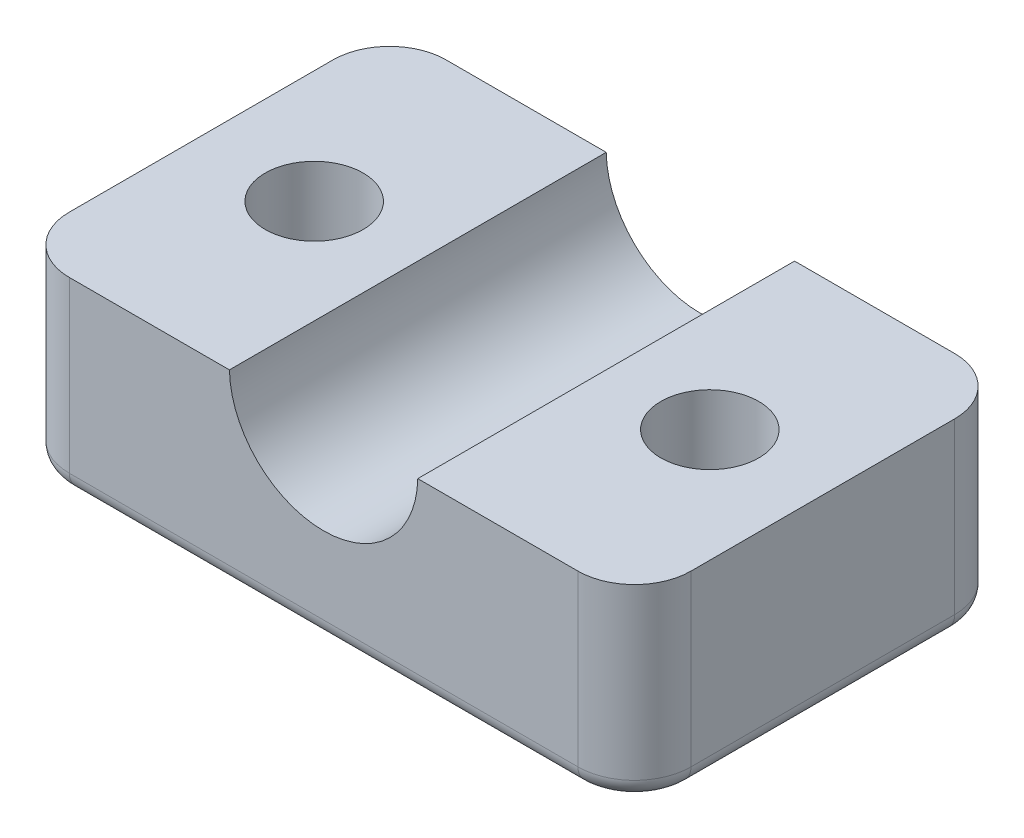
SolidWorks part; units mm, degrees
material "ABS"
ref_plane "Front Plane" through (0, 0, 0) normal (0, 0, 1) x (1, 0, 0)
ref_plane "Top Plane" through (0, 0, 0) normal (0, 1, 0) x (1, 0, 0)
ref_plane "Right Plane" through (0, 0, 0) normal (1, 0, 0) x (0, 0, -1)
sketch "Sketch1" plane through (0, 0, 0) normal (0, 1, 0) x (1, 0, 0)
  line L0 (-50.7915, 0) -> (50.7915, 0) construction
  line L1 (0, -10) -> (0, 10) construction
  line L2 (-13.5, -10) -> (13.5, -10)
  line L3 (-16.5, -7) -> (-16.5, 7)
  line L4 (-13.5, 10) -> (13.5, 10)
  line L5 (16.5, -7) -> (16.5, 7)
  line L6 (-16.5, -10) -> (16.5, 10) construction
  line L7 (-16.5, 10) -> (16.5, -10) construction
  arc A0 (-16.5, -7) -> (-13.5, -10) centre (-13.5, -7) ccw
  arc A1 (13.5, -10) -> (16.5, -7) centre (13.5, -7) ccw
  arc A2 (16.5, 7) -> (13.5, 10) centre (13.5, 7) ccw
  arc A3 (-13.5, 10) -> (-16.5, 7) centre (-13.5, 7) ccw
  circle A4 centre (10.5, 0) radius 2.6
  circle A5 centre (-10.5, 0) radius 2.6
  point P3 (0, 0)
  dimension "D3" = 3
  dimension "D4" = 5.2
  dimension "D5" = 10.5
  dimension "D1" = 33
  dimension "D2" = 20
extrude "Boss-Extrude3" add sketch "Sketch1" along normal blind 10
sketch "Sketch5" plane through (0, 0, -10) normal (0, 0, -1) x (-1, 0, 0)
  line L0 (0, 0) -> (0, 17.6887) construction
  line L1 (-13.5, 0) -> (13.5, 0) construction
  circle A0 centre (0, 10.1) radius 5
  dimension "D1" = 10.1
  dimension "D2" = 10
extrude "Cut-Extrude3" cut sketch "Sketch5" against normal up to surface (20 mm away) up to face at (0, 5, 10)
fillet "Fillet2" radius 1 8 edges at (-15.6213, 0, 9.1213) (-16.5, 0, 0) (-15.6213, 0, -9.1213) (0, 0, -10) (15.6213, 0, -9.1213) (16.5, 0, 0) (15.6213, 0, 9.1213) (0, 0, 10)
